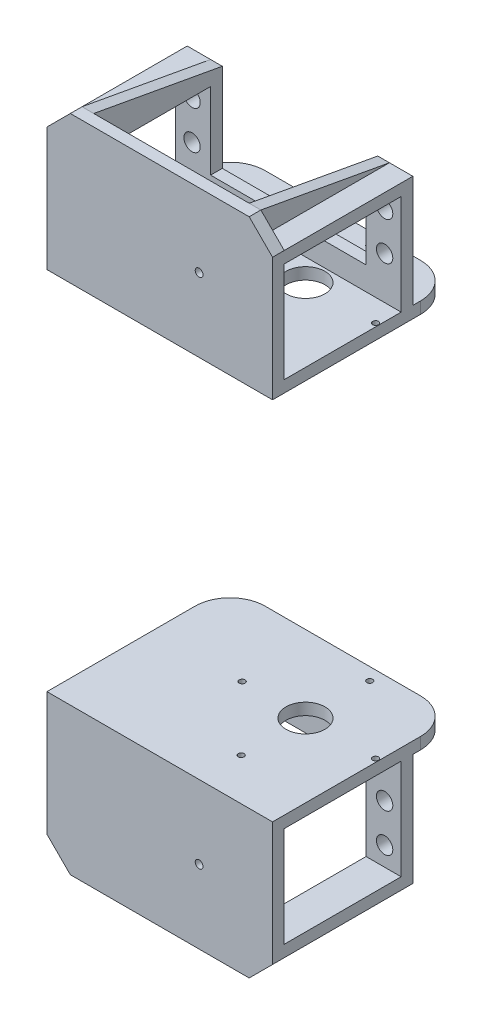
SolidWorks part; units mm, degrees
ref_plane "前视基准面" through (0, 0, 0) normal (0, 0, 1) x (1, 0, 0)
ref_plane "上视基准面" through (0, 0, 0) normal (0, 1, 0) x (1, 0, 0)
ref_plane "右视基准面" through (0, 0, 0) normal (1, 0, 0) x (0, 0, -1)
sketch "草图1" plane through (0, 0, 0) normal (0, 0, 1) x (1, 0, 0)
  line L0 (-4.8606, 17.287) -> (-4.8606, -2.413) construction
  line L1 (-14.7106, 17.287) -> (25.1894, 17.287)
  line L2 (-14.7106, 17.287) -> (-14.7106, -2.413)
  line L3 (-14.7106, -2.413) -> (25.1894, -2.413)
  line L4 (25.1894, 17.287) -> (25.1894, -2.413)
  line L5 (-23.7106, 26.287) -> (34.1894, 26.287)
  line L6 (-23.7106, 26.287) -> (-23.7106, -11.413)
  line L7 (-23.7106, -11.413) -> (34.1894, -11.413)
  line L8 (34.1894, 26.287) -> (34.1894, -11.413)
  line L9 (-14.7106, 7.437) -> (-4.8606, 7.437) construction
  line L10 (-14.7106, 17.287) -> (-23.7106, 17.287) construction
  line L12 (-14.7106, -2.413) -> (-23.7106, -2.413) construction
  line L14 (-14.7106, 17.287) -> (-14.7106, 26.287) construction
  line L16 (25.1894, 17.287) -> (25.1894, 26.287) construction
  circle A0 centre (-19.4706, 12.357) radius 2.1
  circle A1 centre (-19.4706, 2.517) radius 2.1
  circle A2 centre (29.9494, 12.357) radius 2.1
  circle A3 centre (29.9494, 2.517) radius 2.1
  dimension "D7" = 4.2
  dimension "D9" = 4.93
  dimension "D10" = 4.2
  dimension "D11" = 4.93
  dimension "D12" = 4.76
  dimension "D13" = 4.2
  dimension "D14" = 4.2
  dimension "D17" = 4.76
  dimension "D1" = 39.9
  dimension "D2" = 19.7
  dimension "D3" = 9
  dimension "D4" = 9
  dimension "D5" = 9
  dimension "D6" = 9
  dimension "D8" = 4.76
  dimension "D15" = 4.93
  dimension "D16" = 4.93
  dimension "D18" = 4.76
  dimension "D19" = 9.85
  dimension "D20" = 9.85
extrude "凸台-拉伸1" add sketch "草图1" along normal blind 3
sketch "草图2" plane through (0, 0, 3) normal (0, 0, 1) x (1, 0, 0)
  line L5 (-14.7106, 17.287) -> (-14.7106, 26.287) construction
  line L6 (-14.7106, 17.287) -> (-14.7106, -2.413) construction
  line L7 (25.1894, 17.287) -> (25.1894, 26.287) construction
  line L8 (34.1894, -11.413) -> (34.1894, 26.287) construction
  line L13 (-23.7106, 26.287) -> (34.1894, 26.287)
  line L14 (-23.7106, 26.287) -> (-23.7106, 23.287)
  line L15 (-23.7106, 23.287) -> (34.1894, 23.287)
  line L16 (34.1894, 26.287) -> (34.1894, 23.287)
extrude "凸台-拉伸2" add sketch "草图2" along normal blind 30
sketch "草图3" plane through (0, 0, 33) normal (0, 0, 1) x (1, 0, 0)
  line L0 (-14.7106, -2.413) -> (-14.7106, 31.6525) construction
  line L1 (25.1894, -2.413) -> (25.1894, 31.6525) construction
  line L2 (-14.7106, -2.413) -> (25.1894, -2.413) construction
  line L3 (-4.8606, -2.413) -> (-4.8606, 17.287) construction
  line L4 (25.1894, 17.287) -> (-14.7106, 17.287) construction
  line L5 (-4.8606, 17.287) -> (-4.8606, 7.437) construction
  line L6 (-4.8606, 7.437) -> (-14.7106, 7.437) construction
  line L7 (-14.7106, 26.287) -> (-23.7106, 26.287)
  line L8 (-14.7106, 26.287) -> (25.1894, 26.287)
  line L12 (-23.7106, 26.287) -> (-23.7106, -2.413)
  line L13 (-23.7106, 23.287) -> (-23.7106, -11.413) construction
  line L15 (25.1894, 26.287) -> (34.1894, 26.287)
  line L16 (34.1894, 26.287) -> (34.1894, -2.413)
  line L17 (34.1894, -11.413) -> (34.1894, 23.287) construction
  line L19 (34.1894, -2.413) -> (34.1894, -5.413)
  line L20 (34.1894, -5.413) -> (-23.7106, -5.413)
  line L21 (-23.7106, -5.413) -> (-23.7106, -2.413)
  circle A1 centre (15.3394, 7.437) radius 1
  dimension "D5" = 9.85
  dimension "D6" = 2
  dimension "D1" = 9.85
  dimension "D2" = 9.85
  dimension "D4" = 3
extrude "凸台-拉伸3" add sketch "草图3" along normal blind 3
sketch "草图9" plane through (0, 0, 0) normal (0, 0, -1) x (-1, 0, 0)
  line L0 (23.7106, 26.287) -> (23.7106, -11.413) construction
  line L1 (-34.1894, 26.287) -> (23.7106, 26.287)
  line L2 (-34.1894, 26.287) -> (-34.1894, 23.287)
  line L3 (-34.1894, 23.287) -> (23.7106, 23.287)
  line L4 (23.7106, 26.287) -> (23.7106, 23.287)
  dimension "D1" = 3
extrude "凸台-拉伸4" add sketch "草图9" along normal blind 11
sketch "草图10" plane through (0, 26.287, 0) normal (0, 1, 0) x (1, 0, 0)
  line L0 (34.1894, -36) -> (34.1894, 11) construction
  line L1 (34.1894, -36) -> (-23.7106, -36) construction
  line L2 (-23.7106, 2) -> (-23.7106, 11)
  line L3 (-23.7106, 11) -> (-14.7106, 11) construction
  line L4 (-23.7106, 11) -> (-23.7106, 2) construction
  line L5 (-23.7106, 2) -> (-14.7106, 2) construction
  line L6 (-14.7106, 11) -> (-14.7106, 2) construction
  line L7 (34.1894, 11) -> (25.1894, 11) construction
  line L8 (34.1894, 11) -> (34.1894, 2) construction
  line L9 (34.1894, 2) -> (25.1894, 2) construction
  line L10 (25.1894, 11) -> (25.1894, 2) construction
  line L11 (-23.7106, 11) -> (-14.7106, 11)
  line L12 (25.1894, 11) -> (34.1894, 11)
  line L13 (34.1894, 11) -> (34.1894, 2)
  line L15 (15.3394, 9.3) -> (15.3394, -26.7) construction
  line L17 (33.3394, -8.7) -> (-2.6606, -8.7) construction
  circle A0 centre (15.3394, -8.7) radius 18 construction
  arc A1 (-23.7106, 2) -> (-14.7106, 11) centre (-14.7106, 2) cw
  arc A2 (25.1894, 11) -> (34.1894, 2) centre (25.1894, 2) cw
  circle A3 centre (15.3394, 7.8) radius 0.75
  circle A5 centre (33.3394, -8.7) radius 0.75
  circle A6 centre (15.3394, -25.2) radius 0.75
  circle A7 centre (-0.9106, -8.7) radius 0.75
  circle A8 centre (15.3394, -8.7) radius 5
  dimension "D1" = 36
  dimension "D2" = 18.85
  dimension "D3" = 27.3
  dimension "D8" = 1.5
  dimension "D9" = 0
  dimension "D11" = 1.5
  dimension "D13" = 1.5
  dimension "D14" = 1.5
  dimension "D4" = 9
  dimension "D5" = 9
  dimension "D6" = 9
  dimension "D7" = 9
  dimension "D10" = 1.5
  dimension "D12" = 1.5
  dimension "D15" = 1.75
  dimension "D24" = 0.85
  dimension "D25" = 0.85
extrude "切除-拉伸3" cut sketch "草图10" against normal blind 3
ref_plane "基准面1" through (0, 73.187, 0) normal (0, 1, 0) x (1, 0, 0)
mirror "镜向1" about plane through (0, 73.187, 0) normal (0, 1, 0) of bodies 113
sketch "草图11" plane through (0, 0, 33) normal (0, 0, -1) x (-1, 0, 0)
  line L0 (-34.1894, -11.413) -> (-34.1894, 23.287) construction
  line L1 (14.7106, -2.413) -> (23.7106, -2.413)
  line L2 (14.7106, -2.413) -> (14.7106, -5.413)
  line L3 (14.7106, -5.413) -> (23.7106, -5.413)
  line L4 (23.7106, -2.413) -> (23.7106, -5.413)
  line L5 (-25.1894, -2.413) -> (-34.1894, -2.413)
  line L6 (-25.1894, -2.413) -> (-25.1894, -5.413)
  line L7 (-25.1894, -5.413) -> (-34.1894, -5.413)
  line L8 (-34.1894, -2.413) -> (-34.1894, -5.413)
extrude "凸台-拉伸5" add sketch "草图11" along normal blind 32
sketch "草图12" plane through (0, 0, 0) normal (0, 0, -1) x (-1, 0, 0)
  line L0 (-25.1894, -2.413) -> (-25.1894, -5.413)
  line L1 (-25.1894, -5.413) -> (-34.1894, -5.413)
  line L2 (-34.1894, -11.413) -> (-34.1894, 23.287) construction
  line L3 (-34.1894, -5.413) -> (-34.1894, -11.413)
  line L4 (-34.1894, -11.413) -> (23.7106, -11.413)
  line L5 (23.7106, -11.413) -> (23.7106, -5.413)
  line L6 (23.7106, 23.287) -> (23.7106, -11.413) construction
  line L7 (23.7106, -5.413) -> (14.7106, -5.413)
  line L8 (14.7106, -5.413) -> (14.7106, -2.413)
  line L9 (14.7106, -2.413) -> (-25.1894, -2.413)
  dimension "D1" = 3
  dimension "D2" = 3
extrude "切除-拉伸4" cut sketch "草图12" against normal blind 9
sketch "草图13" plane through (0, 0, 36) normal (0, 0, 1) x (1, 0, 0)
  line L0 (-23.7106, -5.413) -> (34.1894, -5.413)
  line L1 (34.1894, -5.413) -> (28.1894, -11.413)
  line L2 (28.1894, -11.413) -> (-17.7106, -11.413)
  line L3 (-17.7106, -11.413) -> (-23.7106, -5.413)
  line L4 (-23.7106, 26.287) -> (-23.7106, -5.413) construction
  line L5 (34.1894, -5.413) -> (34.1894, 26.287) construction
  dimension "D1" = 6
  dimension "D2" = 6
  dimension "D3" = 6
extrude "凸台-拉伸6" add sketch "草图13" against normal blind 3
sketch "草图17" plane through (0, -5.413, 0) normal (0, -1, 0) x (1, 0, 0)
  line L1 (-17.7106, 33) -> (-14.7106, 33)
  line L2 (-17.7106, 33) -> (-17.7106, 0)
  line L3 (-17.7106, 0) -> (-14.7106, 0)
  line L4 (-14.7106, 33) -> (-14.7106, 0)
  line L6 (28.1894, 33) -> (25.1894, 33)
  line L7 (28.1894, 33) -> (28.1894, 0)
  line L8 (28.1894, 0) -> (25.1894, 0)
  line L9 (25.1894, 33) -> (25.1894, 0)
extrude "凸台-拉伸7" add sketch "草图17" along normal blind 6
sketch "草图19" plane through (-17.7106, 0, 0) normal (-1, 0, 0) x (0, 0, 1)
  line L0 (0, -5.413) -> (0, -11.413)
  line L1 (0, -11.413) -> (33, -11.413)
  line L2 (33, -11.413) -> (0, -5.413)
extrude "切除-拉伸5" cut sketch "草图19" against normal blind 52
delete or keep bodies "实体-删除/保留 1" type delete bodies bodies 114
mirror "镜向2" about plane through (0, 73.187, 0) normal (0, 1, 0) of bodies 119
